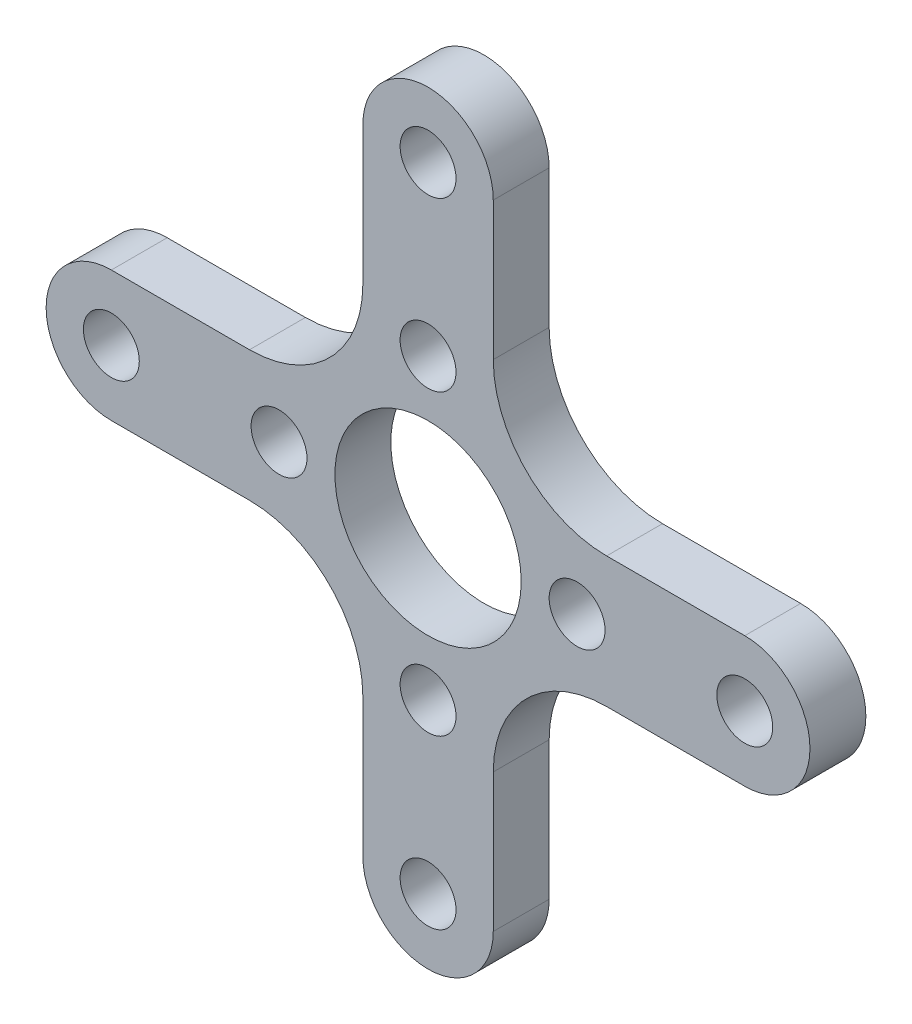
SolidWorks part; units mm, degrees
ref_plane "Front" through (0, 0, 0) normal (0, 0, 1) x (1, 0, 0)
ref_plane "Top" through (0, 0, 0) normal (0, 1, 0) x (1, 0, 0)
ref_plane "Right" through (0, 0, 0) normal (1, 0, 0) x (0, 0, -1)
sketch "Sketch1" plane through (0, 0, 0) normal (0, 0, 1) x (1, 0, 0)
  line L0 (0, 5) -> (0, 79.024) construction
  line L1 (-3.5, 9.5844) -> (-3.5, 17)
  line L4 (3.5, 9.5844) -> (3.5, 17)
  line L5 (9.5844, 3.5) -> (17, 3.5)
  line L6 (9.5844, -3.5) -> (17, -3.5)
  line L7 (3.5, -9.5844) -> (3.5, -17)
  line L8 (-3.5, -9.5844) -> (-3.5, -17)
  line L9 (-9.5844, -3.5) -> (-17, -3.5)
  line L10 (-9.5844, 3.5) -> (-17, 3.5)
  line L11 (0, 0) -> (-7.6225, 7.6225) construction
  line L12 (0, 0) -> (-8.2717, 0) construction
  line L13 (0, 0) -> (17, 0) construction
  circle A0 centre (0, 0) radius 5
  arc A3 (-3.5, 17) -> (3.5, 17) centre (0, 17) cw
  arc A4 (17, 3.5) -> (17, -3.5) centre (17, 0) cw
  arc A5 (3.5, -17) -> (-3.5, -17) centre (0, -17) cw
  arc A6 (-17, -3.5) -> (-17, 3.5) centre (-17, 0) cw
  arc A7 (-9.5844, 3.5) -> (-3.5, 9.5844) centre (-9.5844, 9.5844) ccw
  arc A8 (3.5, 9.5844) -> (9.5844, 3.5) centre (9.5844, 9.5844) ccw
  arc A9 (9.5844, -3.5) -> (3.5, -9.5844) centre (9.5844, -9.5844) ccw
  arc A10 (-3.5, -9.5844) -> (-9.5844, -3.5) centre (-9.5844, -9.5844) ccw
  circle A11 centre (8, 0) radius 1.5
  circle A12 centre (17, 0) radius 1.5
  point P9 (0, 20.5)
  point P11 (0, -20.5)
  point P12 (-3.5355, 3.5355)
  point P18 (18.5, 0)
  point P20 (20.5, 0)
  point P23 (15.5, 0)
  point P25 (9.5, 0)
  point P28 (0, 0)
  point P34 (-5.2821, 5.2821)
  point P47 (0, 0)
  dimension "D1" = 41
  dimension "D2" = 10
  dimension "D3" = 45
  dimension "D4" = 2.47
  dimension "D8" = 2
  dimension "D9" = 3
  dimension "D11" = 3
  dimension "D7" = 7
  dimension "D10" = 6
  dimension "D5" = 4
  dimension "D6" = 4
extrude "Boss-Extrude1" add sketch "Sketch1" along normal blind 3
sketch "Sketch2" plane through (0, 0, 3) normal (0, 0, 1) x (1, 0, 0)
  line L0 (0, 0) -> (8, 0) construction
  circle A0 centre (17, 0) radius 1.5 construction
  circle A1 centre (8, 0) radius 1.5 construction
  circle A2 centre (17, 0) radius 1.5
  circle A3 centre (8, 0) radius 1.5
  circle A4 centre (0, -8) radius 1.5
  circle A5 centre (0, -17) radius 1.5
  circle A6 centre (-8, 0) radius 1.5
  circle A7 centre (-17, 0) radius 1.5
  circle A8 centre (0, 8) radius 1.5
  circle A9 centre (0, 17) radius 1.5
  dimension "D1" = 8
extrude "Cut-Extrude1" cut sketch "Sketch2" against normal blind 3
